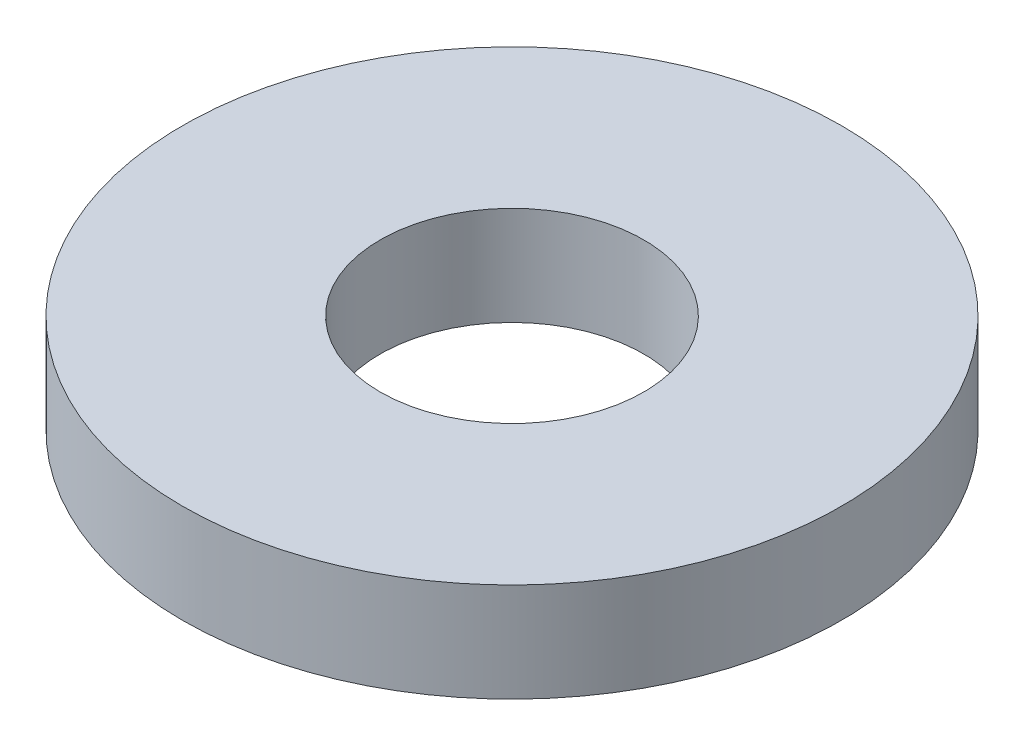
SolidWorks part; units mm, degrees
ref_plane "Alzado" through (0, 0, 0) normal (0, 0, 1) x (1, 0, 0)
ref_plane "Planta" through (0, 0, 0) normal (0, 1, 0) x (1, 0, 0)
ref_plane "Vista lateral" through (0, 0, 0) normal (1, 0, 0) x (0, 0, -1)
sketch "Croquis1" plane through (0, 0, 0) normal (0, 1, 0) x (1, 0, 0)
  circle A0 centre (0, 0) radius 10
  circle A1 centre (0, 0) radius 4
  dimension "D1" = 8
  dimension "D2" = 20
extrude "Saliente-Extruir1" add sketch "Croquis1" along normal blind 3
